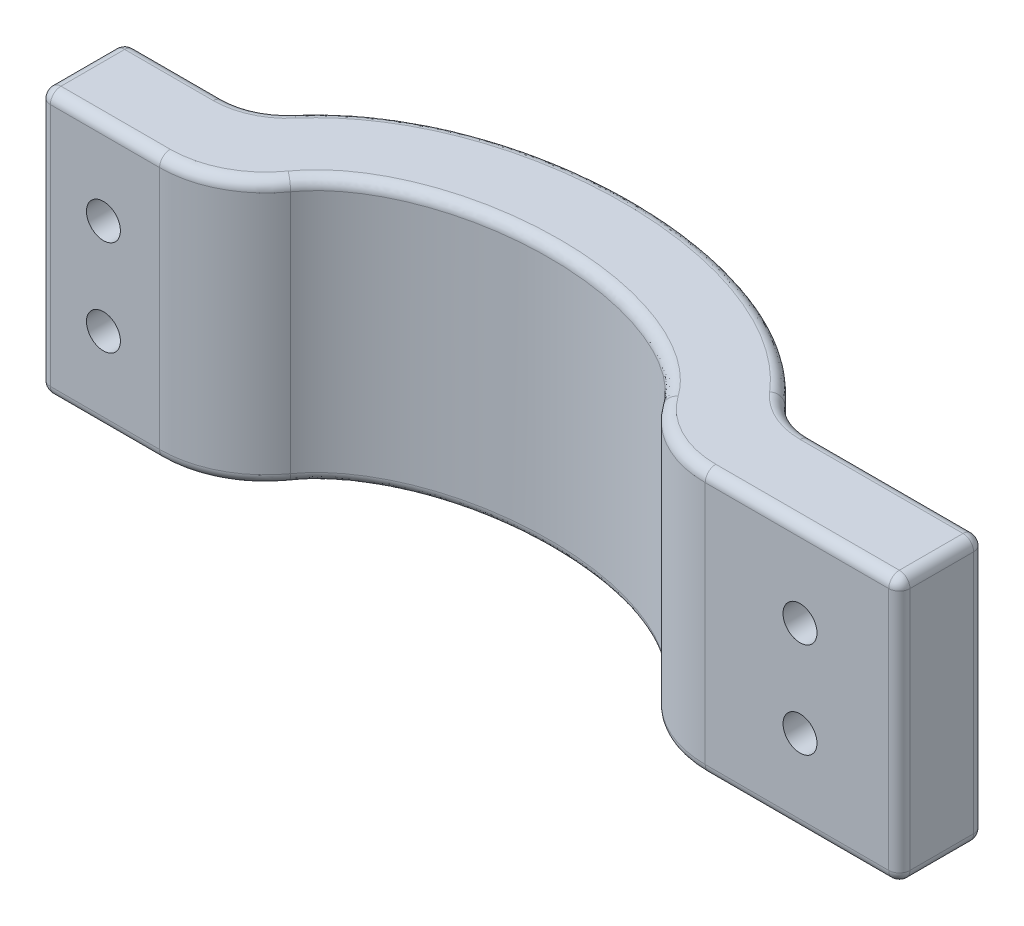
SolidWorks part; units mm, degrees
ref_plane "Front Plane" through (0, 0, 0) normal (0, 0, 1) x (1, 0, 0)
ref_plane "Top Plane" through (0, 0, 0) normal (0, 1, 0) x (1, 0, 0)
ref_plane "Right Plane" through (0, 0, 0) normal (1, 0, 0) x (0, 0, -1)
sketch "Sketch1" plane through (0, 0, 0) normal (0, 1, 0) x (1, 0, 0)
  line L0 (-37, 8) -> (-24.6393, 8)
  line L5 (-37, 0) -> (-19, 0)
  line L6 (-37, 8) -> (-37, 0)
  line L7 (44, 8) -> (44, 0)
  line L8 (19, 0) -> (44, 0)
  line L9 (24.6393, 8) -> (44, 8)
  ellipse E0 centre (0, 0) end of major axis (19, 0) minor radius 11 (19, 0) -> (-19, 0) ccw
  spline S1 degree 3 poles (24.6393, 8) (24.4542, 8.2955) (23.4089, 9.8528) (21.1273, 12.2824) (16.3039, 15.6462) (9.2775, 18.2961) (0, 19.3519) (-9.2775, 18.2961) (-16.3039, 15.6462) (-21.1273, 12.2824) (-23.4089, 9.8528) (-24.4542, 8.2955) (-24.6393, 8) knots 0.348101 0.348101 0.348101 0.348101 0.392699 0.589049 0.785398 1.178097 1.570796 1.963495 2.356194 2.552544 2.748894 2.793492 2.793492 2.793492 2.793492
  dimension "D1" = 38
  dimension "D2" = 22
  dimension "D4" = 8
  dimension "D3" = 18
  dimension "D5" = 25
extrude "Boss-Extrude2" add sketch "Sketch1" along normal blind 25
sketch "Sketch3" plane through (0, 0, -8) normal (0, 0, -1) x (-1, 0, 0)
  line L0 (24.6393, 25) -> (37, 25) construction
  line L1 (37, 25) -> (37, 0) construction
  line L2 (24.6393, 0) -> (37, 0) construction
  line L3 (-44, 25) -> (-24.6393, 25) construction
  line L4 (-24.6393, 25) -> (-24.6393, 0) construction
  line L5 (-44, 0) -> (-24.6393, 0) construction
  circle A0 centre (31, 17) radius 1.6
  circle A1 centre (31, 8) radius 1.6
  circle A2 centre (-34.6393, 17) radius 1.6
  circle A3 centre (-34.6393, 8) radius 1.6
  point P18 (0, 0)
  dimension "D1" = 3.2
  dimension "D2" = 3.2
  dimension "D7" = 3.2
  dimension "D8" = 3.2
  dimension "D3" = 8
  dimension "D4" = 6
  dimension "D5" = 8
  dimension "D6" = 6
  dimension "D9" = 8
  dimension "D10" = 10
  dimension "D11" = 8
  dimension "D12" = 10
extrude "Cut-Extrude1" cut sketch "Sketch3" against normal through all
fillet "Fillet1" radius 10 2 edges at (-19, 12.5, 0) (19, 12.5, 0)
fillet "Fillet2" radius 6 2 edges at (-24.6393, 12.5, -8) (24.6393, 12.5, -8)
fillet "Fillet3" radius 1 32 edges at (44, 12.5, 0) (-37, 12.5, 0) (-37, 25, -4) (-25.1429, 25, -8.5492) (25.1429, 25, -8.5492) (44, 25, -4) (34.8533, 25, 0) (21.1263, 25, -1.1107) (0, 25, -11) (-21.1263, 25, -1.1107) (-31.3533, 25, 0) (21.1263, 0, -1.1107) (34.8533, 0, 0) (44, 0, -4) (25.1429, 0, -8.5492) (-25.1429, 0, -8.5492) (-37, 0, -4) (-31.3533, 0, 0) (-21.1263, 0, -1.1107) (0, 0, -11) (-37, 12.5, -8) (-32.3253, 0, -8) (-32.3253, 25, -8) (-32.6, 17, -8) (-32.6, 8, -8) (44, 12.5, -8) (35.8253, 25, -8) (35.8253, 0, -8) (33.0393, 8, -8) (33.0393, 17, -8)
